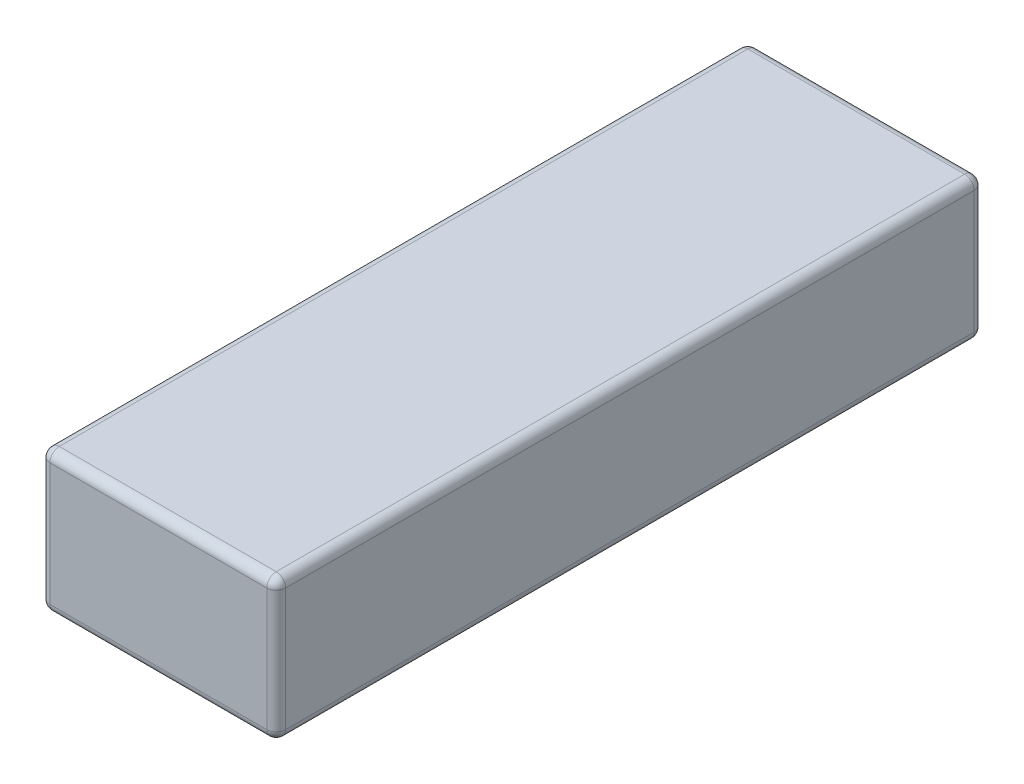
SolidWorks part; units mm, degrees
ref_plane "Front Plane" through (0, 0, 0) normal (0, 0, 1) x (1, 0, 0)
ref_plane "Top Plane" through (0, 0, 0) normal (0, 1, 0) x (1, 0, 0)
ref_plane "Right Plane" through (0, 0, 0) normal (1, 0, 0) x (0, 0, -1)
sketch "Sketch2" plane through (0, 0, 0) normal (0, 1, 0) x (1, 0, 0)
  line L1 (-25, 75) -> (25, 75)
  line L2 (-25, 75) -> (-25, -75)
  line L3 (-25, -75) -> (25, -75)
  line L4 (25, 75) -> (25, -75)
  line L5 (-25, 75) -> (25, -75) construction
  line L6 (-25, -75) -> (25, 75) construction
  point P0 (0, 0)
  dimension "D1" = 50
  dimension "D2" = 150
extrude "Boss-Extrude1" add sketch "Sketch2" along normal blind 30
fillet "Fillet1" radius 2 12 edges at (25, 0, 0) (25, 15, 75) (0, 0, 75) (25, 15, -75) (0, 0, -75) (0, 30, 75) (0, 30, -75) (25, 30, 0) (-25, 15, -75) (-25, 30, 0) (-25, 15, 75) (-25, 0, 0)
